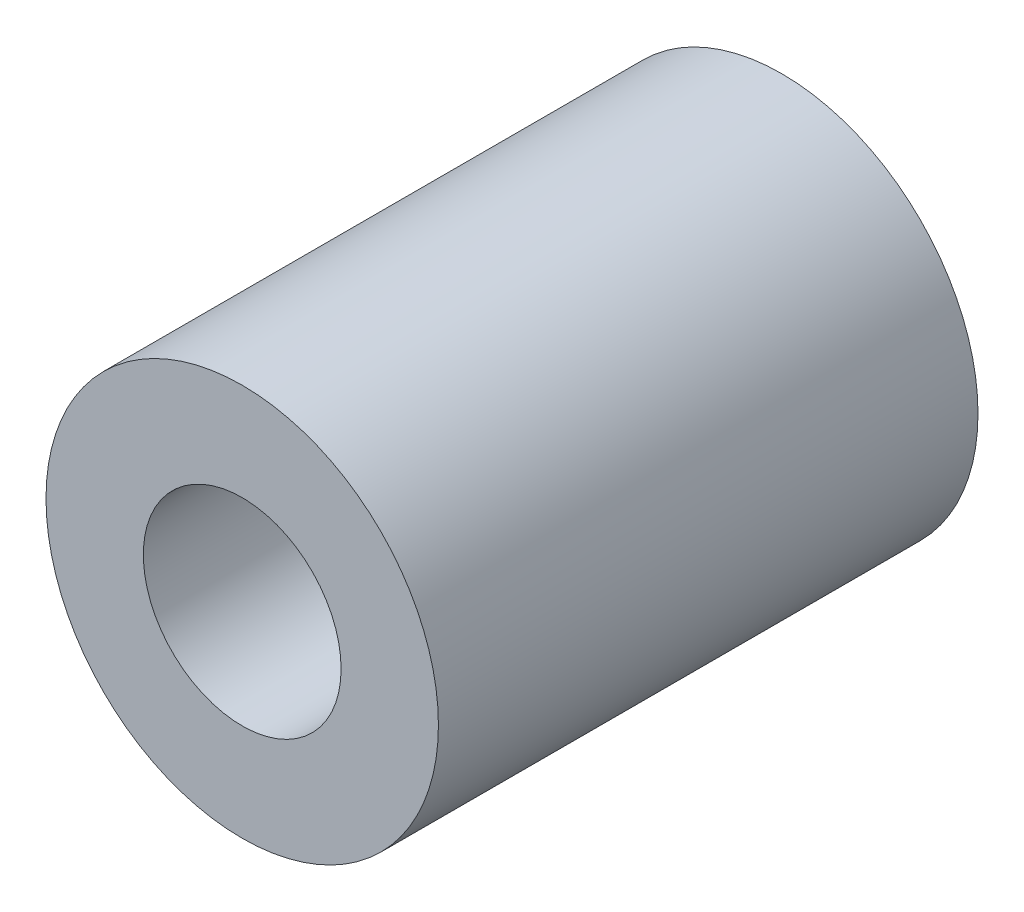
SolidWorks part; units mm, degrees
ref_plane "Front Plane" through (0, 0, 0) normal (0, 0, 1) x (1, 0, 0)
ref_plane "Top Plane" through (0, 0, 0) normal (0, 1, 0) x (1, 0, 0)
ref_plane "Right Plane" through (0, 0, 0) normal (1, 0, 0) x (0, 0, -1)
sketch "Sketch1" plane through (0, 0, 0) normal (0, 0, 1) x (1, 0, 0)
  circle A0 centre (0, 0) radius 6.35
  circle A1 centre (0, 0) radius 3.2004
  dimension "OD" = 12.7
  dimension "ID" = 6.4008
extrude "Extrude1" add sketch "Sketch1" along normal mid plane 17.4625
sketch "Sketch2" plane through (0, 0, 0) normal (1, 0, 0) x (0, 0, -1)
  line L0 (-8.7312, -3.2004) -> (8.7312, -3.2004) construction
  line L3 (8.7312, 3.2004) -> (-8.7312, 3.2004) construction
  line L5 (-8.7312, -3.2004) -> (8.7312, -3.2004)
  line L6 (8.7312, 3.2004) -> (-8.7312, 3.2004)
sketch "Sketch4" plane through (0, 0, 8.7312) normal (0, 0, 1) x (1, 0, 0)
  line L0 (0, 0) -> (-2.263, 2.263)
  line L1 (0, -5.2388) -> (0, 5.2388) construction
  circle A0 centre (0, 0) radius 3.2004 construction
  dimension "D1" = 45
